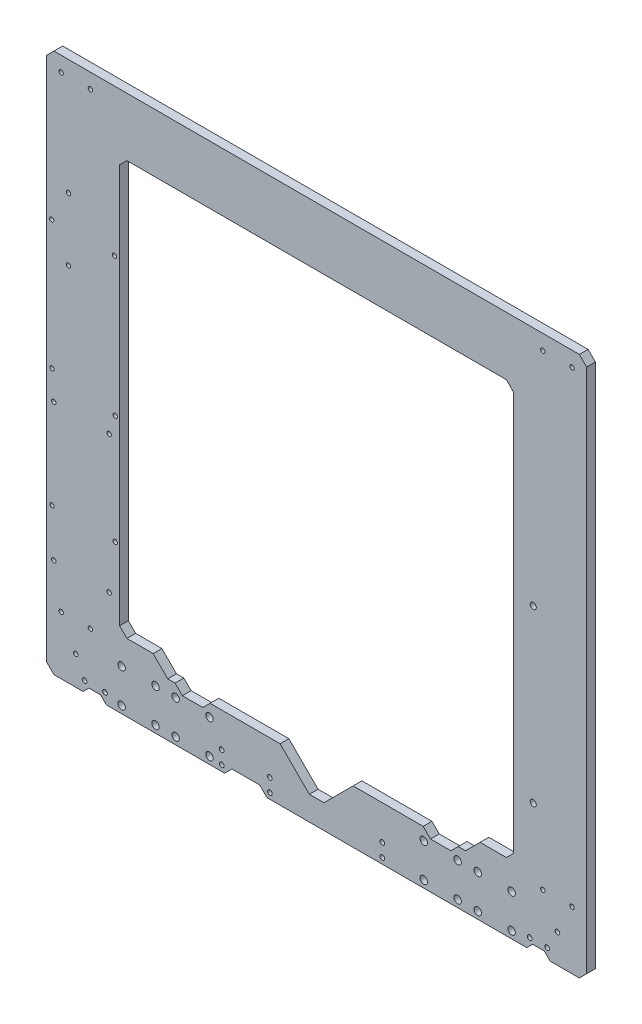
SolidWorks part; units mm, degrees
ref_plane "Přední rovina" through (0, 0, 0) normal (0, 0, 1) x (1, 0, 0)
ref_plane "Horní rovina" through (0, 0, 0) normal (0, 1, 0) x (1, 0, 0)
ref_plane "Pravá rovina" through (0, 0, 0) normal (1, 0, 0) x (0, 0, -1)
sketch "Skica1" plane through (0, 0, 0) normal (0, 0, 1) x (1, 0, 0)
  line L0 (320, 51.5) -> (320, 325)
  line L1 (320, 325) -> (315, 330)
  line L2 (315, 330) -> (55, 330)
  line L3 (320, 51.5) -> (315, 46.5)
  line L4 (315, 46.5) -> (297, 46.5)
  line L5 (297, 46.5) -> (287, 36.5)
  line L6 (287, 36.5) -> (282, 36.5)
  line L7 (282, 36.5) -> (277, 31.5)
  line L8 (277, 31.5) -> (263, 31.5)
  line L9 (263, 31.5) -> (258, 36.5)
  line L10 (258, 36.5) -> (210, 36.5)
  line L11 (210, 36.5) -> (190, 16.5)
  line L12 (190, 16.5) -> (180, 16.5)
  line L13 (50, 325) -> (55, 330)
  line L16 (41, 0) -> (122, 0)
  line L17 (122, 0) -> (127, 5)
  line L19 (127, 5) -> (146, 5)
  line L20 (146, 5) -> (151, 0)
  line L21 (151, 0) -> (329, 0)
  line L22 (329, 0) -> (333, 4)
  line L23 (333, 4) -> (341, 4)
  line L24 (341, 4) -> (345, 0)
  line L25 (345, 0) -> (365, 0)
  line L26 (365, 0) -> (370, 5)
  line L27 (370, 5) -> (370, 365)
  line L28 (370, 365) -> (365, 370)
  line L29 (0, 365) -> (5, 370)
  line L30 (0, 5) -> (0, 365)
  line L31 (5, 0) -> (0, 5)
  line L32 (25, 0) -> (5, 0)
  line L33 (29, 4) -> (25, 0)
  line L34 (37, 4) -> (29, 4)
  line L35 (41, 0) -> (37, 4)
  line L36 (160, 36.5) -> (180, 16.5)
  line L37 (112, 36.5) -> (160, 36.5)
  line L38 (107, 31.5) -> (112, 36.5)
  line L39 (93, 31.5) -> (107, 31.5)
  line L40 (88, 36.5) -> (93, 31.5)
  line L41 (83, 36.5) -> (88, 36.5)
  line L42 (73, 46.5) -> (83, 36.5)
  line L43 (55, 46.5) -> (73, 46.5)
  line L44 (50, 51.5) -> (55, 46.5)
  line L45 (50, 325) -> (50, 51.5)
  line L47 (5, 370) -> (365, 370)
  circle A0 centre (111.6, 4.9) radius 2.55
  circle A1 centre (111.6, 28.1) radius 2.55
  circle A2 centre (258.4, 28.1) radius 2.55
  circle A3 centre (258.4, 4.9) radius 2.55
  circle A4 centre (88.4, 28.1) radius 2.55
  circle A5 centre (88.4, 4.9) radius 2.55
  circle A6 centre (74.6, 4.9) radius 2.55
  circle A7 centre (74.6, 28.1) radius 2.55
  circle A8 centre (51.4, 28.1) radius 2.55
  circle A9 centre (51.4, 4.9) radius 2.55
  circle A10 centre (281.6, 28.1) radius 2.55
  circle A11 centre (281.6, 4.9) radius 2.55
  circle A12 centre (295.4, 4.9) radius 2.55
  circle A13 centre (318.6, 4.9) radius 2.55
  circle A14 centre (318.6, 28.1) radius 2.55
  circle A15 centre (295.4, 28.1) radius 2.55
  circle A16 centre (3.7, 99.8) radius 1.5
  circle A17 centre (47, 99.8) radius 1.5
  circle A18 centre (42.9, 67.8) radius 1.5
  circle A19 centre (4.9, 67.8) radius 1.5
  circle A20 centre (30, 39.8) radius 1.5
  circle A21 centre (10, 39.8) radius 1.5
  circle A22 centre (20, 19.8) radius 1.5
  circle A23 centre (340, 39.8) radius 1.5
  circle A24 centre (360, 39.8) radius 1.5
  circle A25 centre (350, 19.8) radius 1.5
  circle A26 centre (340, 359.8) radius 1.5
  circle A27 centre (360, 359.8) radius 1.5
  circle A28 centre (10, 359.8) radius 1.5
  circle A29 centre (30, 359.8) radius 1.5
  circle A30 centre (15, 247.8) radius 1.5
  circle A31 centre (3.5, 269.3) radius 1.5
  circle A32 centre (46.5, 269.3) radius 1.5
  circle A33 centre (15, 290.8) radius 1.5
  circle A34 centre (4.9, 161.8) radius 1.5
  circle A35 centre (3.7, 181.1) radius 1.5
  circle A36 centre (42.9, 161.8) radius 1.5
  circle A37 centre (47, 174.7) radius 1.5
  circle A38 centre (26, 7) radius 1.6
  circle A39 centre (40, 7) radius 1.6
  circle A40 centre (120, 4) radius 1.6
  circle A41 centre (120, 13) radius 1.6
  circle A42 centre (153, 13) radius 1.6
  circle A43 centre (153, 4) radius 1.6
  circle A44 centre (230, 13) radius 1.6
  circle A45 centre (230, 4) radius 1.6
  circle A46 centre (331, 7) radius 1.6
  circle A47 centre (343, 7) radius 1.6
  circle A48 centre (350, 19.8) radius 1.6
  circle A49 centre (333.4, 88) radius 2.1
  circle A50 centre (333.4, 205) radius 2.1
  dimension "D1" = 370
  dimension "D2" = 370
extrude "Přidat vysunutím1" add sketch "Skica1" against normal blind 6 contours L47 L29 L30 L31 L32 L33 L34 L35 L16 L17 L19 L20 L21 L22 L23 L24 L25 L26 L27 L28 A50 A49 A48 A47 A46 A45 A44 A43 A42 A41 A40 A39 A38 A37 A36
ref_plane "Plane1" through (185, 0, 0) normal (1, 0, 0) x (0, 0, -1)
ref_plane "Plane2" through (0, 185, 0) normal (0, 1, 0) x (1, 0, 0)
ref_plane "Plane3" through (0, 0, -3) normal (0, 0, 1) x (1, 0, 0)
